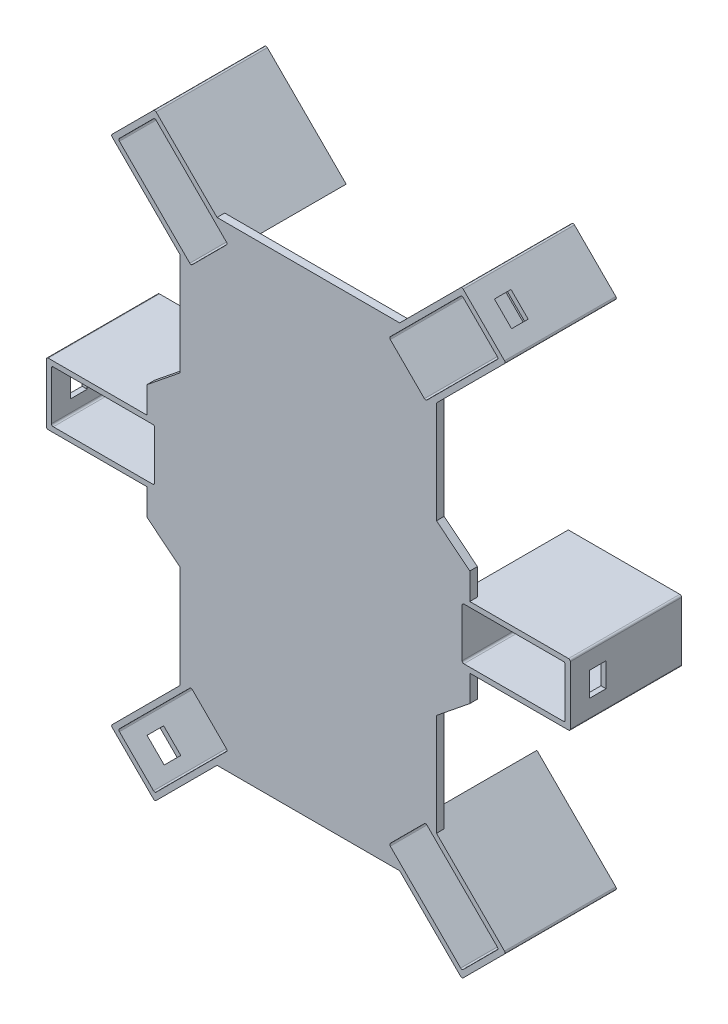
SolidWorks part; units mm, degrees
ref_plane "前视基准面" through (0, 0, 0) normal (0, 0, 1) x (1, 0, 0)
ref_plane "上视基准面" through (0, 0, 0) normal (0, 1, 0) x (1, 0, 0)
ref_plane "右视基准面" through (0, 0, 0) normal (1, 0, 0) x (0, 0, -1)
sketch "草图1" plane through (0, 0, 0) normal (0, 0, 1) x (1, 0, 0)
  line L0 (42.5, 0) -> (90.5, 0) construction
  line L1 (-42.5, 82.5) -> (42.5, 82.5)
  line L2 (-42.5, 82.5) -> (-42.5, -82.5)
  line L3 (-42.5, -82.5) -> (42.5, -82.5)
  line L4 (42.5, 82.5) -> (42.5, -82.5)
  line L5 (-42.5, 82.5) -> (42.5, -82.5) construction
  line L6 (-42.5, -82.5) -> (42.5, 82.5) construction
  line L7 (42.5, 82.5) -> (60.1777, 100.1777) construction
  line L8 (42.5, -82.5) -> (60.1777, -100.1777) construction
  line L9 (-42.5, 0) -> (-90.5, 0) construction
  line L10 (-42.5, -82.5) -> (-60.1777, -100.1777) construction
  line L11 (-42.5, 82.5) -> (-60.1777, 100.1777) construction
  line L12 (58.25, 12.15) -> (102.65, 12.15)
  line L13 (60.25, 10.15) -> (100.65, 10.15)
  line L14 (60.25, 10.15) -> (60.25, -10.15)
  line L15 (60.25, -10.15) -> (100.65, -10.15)
  line L16 (100.65, 10.15) -> (100.65, -10.15)
  line L17 (60.25, 10.15) -> (100.65, -10.15) construction
  line L18 (60.25, -10.15) -> (100.65, 10.15) construction
  line L19 (102.65, 12.15) -> (102.65, -12.15)
  line L20 (58.25, -12.15) -> (102.65, -12.15)
  line L21 (58.25, 12.15) -> (58.25, -12.15)
  line L22 (0, 0) -> (0, 51.9271) construction
  line L23 (-60.25, -10.15) -> (-100.65, 10.15) construction
  line L24 (-60.25, 10.15) -> (-100.65, -10.15) construction
  line L25 (-42.5, 0) -> (-90.5, 0) construction
  line L26 (-58.25, 12.15) -> (-58.25, -12.15)
  line L27 (-58.25, -12.15) -> (-102.65, -12.15)
  line L28 (-102.65, 12.15) -> (-102.65, -12.15)
  line L29 (-100.65, 10.15) -> (-100.65, -10.15)
  line L30 (-60.25, -10.15) -> (-100.65, -10.15)
  line L31 (-60.25, 10.15) -> (-60.25, -10.15)
  line L32 (-60.25, 10.15) -> (-100.65, 10.15)
  line L33 (-58.25, 12.15) -> (-102.65, 12.15)
  point P0 (0, 0)
  point P12 (80.45, 0)
  point P29 (-80.45, 0)
  dimension "D1" = 85
  dimension "D2" = 165
  dimension "D3" = 48
  dimension "D4" = 25
  dimension "D5" = 25
  dimension "D6" = 135
  dimension "D8" = 25
  dimension "D9" = 25
  dimension "D10" = 40.4
  dimension "D11" = 20.3
  dimension "D12" = 10.15
  dimension "D13" = 2
sketch "草图5" plane through (0, 0, 0) normal (0, 0, 1) x (1, 0, 0)
  line L0 (60.1777, 114.5319) -> (74.5319, 100.1777)
  line L1 (74.5319, 100.1777) -> (45.9648, 71.6106)
  line L2 (45.9648, 71.6106) -> (31.6106, 85.9648)
  line L3 (31.6106, 85.9648) -> (60.1777, 114.5319)
  line L4 (60.1777, 100.1777) -> (42.5, 82.5) construction
  line L5 (28.7821, 85.9648) -> (60.1777, 117.3604)
  line L6 (60.1777, 117.3604) -> (77.3604, 100.1777)
  line L7 (77.3604, 100.1777) -> (45.9648, 68.7821)
  line L8 (45.9648, 68.7821) -> (28.7821, 85.9648)
  line L9 (0, 0) -> (28.7821, 0) construction
  line L10 (60.1777, -100.1777) -> (42.5, -82.5) construction
  line L11 (45.9648, -68.7821) -> (28.7821, -85.9648)
  line L12 (77.3604, -100.1777) -> (45.9648, -68.7821)
  line L13 (60.1777, -117.3604) -> (77.3604, -100.1777)
  line L14 (28.7821, -85.9648) -> (60.1777, -117.3604)
  line L15 (31.6106, -85.9648) -> (60.1777, -114.5319)
  line L16 (45.9648, -71.6106) -> (31.6106, -85.9648)
  line L17 (74.5319, -100.1777) -> (45.9648, -71.6106)
  line L18 (60.1777, -114.5319) -> (74.5319, -100.1777)
  line L19 (0, 0) -> (0, 63.0262) construction
  line L20 (-60.1777, -100.1777) -> (-42.5, -82.5) construction
  line L21 (-60.1777, 100.1777) -> (-42.5, 82.5) construction
  line L22 (-60.1777, -114.5319) -> (-74.5319, -100.1777)
  line L23 (-74.5319, -100.1777) -> (-45.9648, -71.6106)
  line L24 (-45.9648, -71.6106) -> (-31.6106, -85.9648)
  line L25 (-31.6106, -85.9648) -> (-60.1777, -114.5319)
  line L26 (-28.7821, -85.9648) -> (-60.1777, -117.3604)
  line L27 (-60.1777, -117.3604) -> (-77.3604, -100.1777)
  line L28 (-77.3604, -100.1777) -> (-45.9648, -68.7821)
  line L29 (-45.9648, -68.7821) -> (-28.7821, -85.9648)
  line L30 (-45.9648, 68.7821) -> (-28.7821, 85.9648)
  line L31 (-77.3604, 100.1777) -> (-45.9648, 68.7821)
  line L32 (-60.1777, 117.3604) -> (-77.3604, 100.1777)
  line L33 (-28.7821, 85.9648) -> (-60.1777, 117.3604)
  line L34 (-31.6106, 85.9648) -> (-60.1777, 114.5319)
  line L35 (-45.9648, 71.6106) -> (-31.6106, 85.9648)
  line L36 (-74.5319, 100.1777) -> (-45.9648, 71.6106)
  line L37 (-60.1777, 114.5319) -> (-74.5319, 100.1777)
  dimension "D1" = 40.4
  dimension "D2" = 20.3
  dimension "D3" = 10.15
  dimension "D4" = 2
extrude "凸台-拉伸5" add sketch "草图1" along normal blind 42 contours L26 L33 L28 L27 L32 L31 L30 L29 | L12 L21 L20 L19 L13 L16 L15 L14 | L2 L3 L4 L1
extrude "凸台-拉伸6" add sketch "草图5" along normal blind 42
sketch "草图6" plane through (0, 0, 0) normal (0, 0, -1) x (-1, 0, 0)
  line L0 (-77.3604, 100.1777) -> (-60.1777, 117.3604)
  line L1 (-60.1777, 117.3604) -> (-28.7821, 85.9648)
  line L2 (-28.7821, 85.9648) -> (-45.9648, 68.7821)
  line L3 (-45.9648, 68.7821) -> (-77.3604, 100.1777)
  line L4 (-60.1777, 100.1777) -> (-55.3693, 95.3693) construction
  line L5 (-42.5, 82.5) -> (-60.1777, 100.1777) construction
  line L6 (-55.3693, 95.3693) -> (-61.0262, 89.7125) construction
  line L7 (-46.0214, 86.0214) -> (-50.9711, 81.0716) construction
  line L8 (-60.1777, 100.1777) -> (-41.0716, 81.0716) construction
  line L9 (-58.25, 12.15) -> (-58.25, -12.15)
  line L10 (-58.25, -12.15) -> (-102.65, -12.15)
  line L11 (-70.48, 0) -> (-70.48, -7) construction
  line L12 (-102.65, 12.15) -> (-58.25, 12.15)
  line L13 (-90.5, 0) -> (-83.7, 0) construction
  line L14 (-83.7, 0) -> (-83.7, -8) construction
  line L15 (-102.65, -12.15) -> (-102.65, 12.15)
  line L16 (-90.5, 0) -> (-63.48, 0) construction
  line L17 (0, 0) -> (28.8174, 0) construction
  line L18 (-60.1777, -100.1777) -> (-41.0716, -81.0716) construction
  line L19 (-46.0214, -86.0214) -> (-50.9711, -81.0716) construction
  line L20 (-55.3693, -95.3693) -> (-61.0262, -89.7125) construction
  line L21 (-60.1777, -100.1777) -> (-55.3693, -95.3693) construction
  line L22 (-45.9648, -68.7821) -> (-77.3604, -100.1777)
  line L23 (-28.7821, -85.9648) -> (-45.9648, -68.7821)
  line L24 (-60.1777, -117.3604) -> (-28.7821, -85.9648)
  line L25 (-77.3604, -100.1777) -> (-60.1777, -117.3604)
  line L26 (0, 0) -> (0, 41.0971) construction
  line L27 (0, 0) -> (0, 51.9271) construction
  line L28 (60.1777, -100.1777) -> (55.3693, -95.3693) construction
  line L29 (55.3693, -95.3693) -> (61.0262, -89.7125) construction
  line L30 (46.0214, -86.0214) -> (50.9711, -81.0716) construction
  line L31 (60.1777, -100.1777) -> (41.0716, -81.0716) construction
  line L32 (90.5, 0) -> (63.48, 0) construction
  line L33 (83.7, 0) -> (83.7, -8) construction
  line L34 (90.5, 0) -> (83.7, 0) construction
  line L35 (70.48, 0) -> (70.48, -7) construction
  line L36 (60.1777, 100.1777) -> (41.0716, 81.0716) construction
  line L37 (46.0214, 86.0214) -> (50.9711, 81.0716) construction
  line L38 (55.3693, 95.3693) -> (61.0262, 89.7125) construction
  line L39 (60.1777, 100.1777) -> (55.3693, 95.3693) construction
  line L40 (77.3604, -100.1777) -> (60.1777, -117.3604)
  line L41 (60.1777, -117.3604) -> (28.7821, -85.9648)
  line L42 (28.7821, -85.9648) -> (45.9648, -68.7821)
  line L43 (45.9648, -68.7821) -> (77.3604, -100.1777)
  line L44 (102.65, -12.15) -> (102.65, 12.15)
  line L45 (102.65, 12.15) -> (58.25, 12.15)
  line L46 (58.25, -12.15) -> (102.65, -12.15)
  line L47 (58.25, 12.15) -> (58.25, -12.15)
  line L48 (45.9648, 68.7821) -> (77.3604, 100.1777)
  line L49 (28.7821, 85.9648) -> (45.9648, 68.7821)
  line L50 (60.1777, 117.3604) -> (28.7821, 85.9648)
  line L51 (77.3604, 100.1777) -> (60.1777, 117.3604)
  circle A0 centre (-60.1777, 100.1777) radius 6.75
  circle A1 centre (-61.0262, 89.7125) radius 0.8
  circle A2 centre (-50.9711, 81.0716) radius 0.8
  circle A3 centre (-41.0716, 81.0716) radius 0.8
  circle A4 centre (-41.0716, 90.9711) radius 0.8
  circle A5 centre (-49.7125, 101.0262) radius 0.8
  circle A6 centre (-70.48, -7) radius 0.8
  circle A7 centre (-63.48, 0) radius 0.8
  circle A8 centre (-90.5, 0) radius 6.75
  circle A9 centre (-83.7, -8) radius 0.8
  circle A10 centre (-70.48, 7) radius 0.8
  circle A11 centre (-83.7, 8) radius 0.8
  circle A12 centre (-49.7125, -101.0262) radius 0.8
  circle A13 centre (-41.0716, -90.9711) radius 0.8
  circle A14 centre (-41.0716, -81.0716) radius 0.8
  circle A15 centre (-50.9711, -81.0716) radius 0.8
  circle A16 centre (-61.0262, -89.7125) radius 0.8
  circle A17 centre (-60.1777, -100.1777) radius 6.75
  circle A18 centre (60.1777, -100.1777) radius 6.75
  circle A19 centre (61.0262, -89.7125) radius 0.8
  circle A20 centre (50.9711, -81.0716) radius 0.8
  circle A21 centre (41.0716, -81.0716) radius 0.8
  circle A22 centre (41.0716, -90.9711) radius 0.8
  circle A23 centre (49.7125, -101.0262) radius 0.8
  circle A24 centre (83.7, 8) radius 0.8
  circle A25 centre (70.48, 7) radius 0.8
  circle A26 centre (83.7, -8) radius 0.8
  circle A27 centre (90.5, 0) radius 6.75
  circle A28 centre (63.48, 0) radius 0.8
  circle A29 centre (70.48, -7) radius 0.8
  circle A30 centre (49.7125, 101.0262) radius 0.8
  circle A31 centre (41.0716, 90.9711) radius 0.8
  circle A32 centre (41.0716, 81.0716) radius 0.8
  circle A33 centre (50.9711, 81.0716) radius 0.8
  circle A34 centre (61.0262, 89.7125) radius 0.8
  circle A35 centre (60.1777, 100.1777) radius 6.75
  dimension "D1" = 13.5
  dimension "D4" = 1.6
  dimension "D7" = 1.6
  dimension "D9" = 1.6
  dimension "D2" = 6.8
  dimension "D3" = 8
  dimension "D5" = 7
  dimension "D6" = 20.02
  dimension "D8" = 27.02
extrude "凸台-拉伸8" add sketch "草图6" along normal blind 1.6
fillet "圆角1" radius 0.7 4 edges at (31.6106, 85.9648, 21) (45.9648, 71.6106, 21) (60.1777, 114.5319, 21) (74.5319, 100.1777, 21)
fillet "圆角2" radius 0.7 4 edges at (-74.5319, 100.1777, 21) (-60.1777, 114.5319, 21) (-45.9648, 71.6106, 21) (-31.6106, 85.9648, 21)
fillet "圆角3" radius 0.7 4 edges at (-60.25, -10.15, 21) (-100.65, -10.15, 21) (-100.65, 10.15, 21) (-60.25, 10.15, 21)
fillet "圆角4" radius 0.7 4 edges at (-60.1777, -114.5319, 21) (-74.5319, -100.1777, 21) (-45.9648, -71.6106, 21) (-31.6106, -85.9648, 21)
fillet "圆角5" radius 0.7 4 edges at (60.1777, -114.5319, 21) (74.5319, -100.1777, 21) (45.9648, -71.6106, 21) (31.6106, -85.9648, 21)
fillet "圆角6" radius 0.7 4 edges at (60.25, 10.15, 21) (60.25, -10.15, 21) (100.65, -10.15, 21) (100.65, 10.15, 21)
sketch "草图7" plane through (0, 0, -1.6) normal (0, 0, -1) x (-1, 0, 0)
  line L0 (0, 0) -> (0, -53.3863) construction
  circle A4 centre (83.7, 8) radius 2
  circle A5 centre (83.7, -8) radius 2
  circle A6 centre (61.0262, -89.7125) radius 2
  circle A7 centre (49.7125, -101.0262) radius 2
  circle A8 centre (-49.7125, -101.0262) radius 2
  circle A9 centre (-61.0262, -89.7125) radius 2
  circle A10 centre (-83.7, -8) radius 2
  circle A11 centre (-83.7, 8) radius 2
  circle A14 centre (-61.0262, 89.7125) radius 2
  circle A15 centre (-49.7125, 101.0262) radius 2
  circle A16 centre (49.7125, 101.0262) radius 2
  circle A17 centre (61.0262, 89.7125) radius 2
  dimension "D3" = 4
  dimension "D4" = 4
  dimension "D5" = 4
  dimension "D6" = 4
  dimension "D7" = 4
  dimension "D8" = 4
  dimension "D9" = 4
  dimension "D10" = 4
extrude "切除-拉伸2" cut sketch "草图7" against normal blind 0.7
sketch "草图8" plane through (-88.769, -88.769, 0) normal (-0.7071, -0.7071, 0) x (0, 0, 1)
  line L0 (-1.6, -28.2843) -> (42, -28.2843) construction
  line L1 (-1.6, -40.4343) -> (-1.6, -16.1343) construction
  line L2 (42, -16.1343) -> (42, -40.4343) construction
  line L4 (28, -23.5343) -> (34.5, -23.5343)
  line L5 (28, -23.5343) -> (28, -33.0343)
  line L6 (28, -33.0343) -> (34.5, -33.0343)
  line L7 (34.5, -23.5343) -> (34.5, -33.0343)
  dimension "D1" = 7.5
  dimension "D2" = 9.5
  dimension "D3" = 6.5
extrude "切除-拉伸3" cut sketch "草图8" against normal blind 9.8
sketch "草图9" plane through (-102.65, 0, 0) normal (-1, 0, 0) x (0, 0, 1)
  line L0 (42, 12.15) -> (42, -12.15) construction
  line L1 (28, 4.75) -> (34.5, 4.75)
  line L2 (28, 4.75) -> (28, -4.75)
  line L3 (28, -4.75) -> (34.5, -4.75)
  line L4 (34.5, 4.75) -> (34.5, -4.75)
  line L5 (42, 0) -> (20.8942, 0) construction
  dimension "D1" = 6.5
  dimension "D2" = 7.5
  dimension "D3" = 9.5
extrude "切除-拉伸4" cut sketch "草图9" against normal blind 9.8
sketch "草图10" plane through (-88.769, 88.769, 0) normal (-0.7071, 0.7071, 0) x (0, 0, 1)
  line L0 (42, 28.2843) -> (10.5352, 28.2843) construction
  line L1 (42, 40.4343) -> (42, 16.1343) construction
  line L3 (28, 33.0559) -> (34.5, 33.0559)
  line L4 (28, 33.0559) -> (28, 23.5559)
  line L5 (28, 23.5559) -> (34.5, 23.5559)
  line L6 (34.5, 33.0559) -> (34.5, 23.5559)
  dimension "D1" = 7.5
  dimension "D2" = 6.5
  dimension "D3" = 9.5
extrude "切除-拉伸5" cut sketch "草图10" against normal blind 9.8
sketch "草图11" plane through (88.769, 88.769, 0) normal (0.7071, 0.7071, 0) x (0, 0, -1)
  line L0 (1.6, 40.4343) -> (1.6, 16.1343) construction
  line L1 (-34.5, 33.0343) -> (-28, 33.0343)
  line L2 (-34.5, 33.0343) -> (-34.5, 23.5343)
  line L3 (-34.5, 23.5343) -> (-28, 23.5343)
  line L4 (-28, 33.0343) -> (-28, 23.5343)
  line L5 (1.6, 28.2843) -> (-24.8278, 28.2843) construction
  line L6 (-42, 16.1343) -> (-42, 40.4343) construction
  dimension "D1" = 6.5
  dimension "D2" = 9.5
  dimension "D3" = 7.5
extrude "切除-拉伸6" cut sketch "草图11" against normal blind 9.8
sketch "草图12" plane through (102.65, 0, 0) normal (1, 0, 0) x (0, 0, -1)
  line L0 (-42, 12.15) -> (-42, -12.15) construction
  line L1 (-34.5, 4.75) -> (-28, 4.75)
  line L2 (-34.5, 4.75) -> (-34.5, -4.75)
  line L3 (-34.5, -4.75) -> (-28, -4.75)
  line L4 (-28, 4.75) -> (-28, -4.75)
  line L5 (-42, 0) -> (-21.0394, 0) construction
  dimension "D1" = 6.5
  dimension "D2" = 7.5
  dimension "D3" = 9.5
extrude "切除-拉伸7" cut sketch "草图12" against normal blind 9.8
sketch "草图13" plane through (88.769, -88.769, 0) normal (0.7071, -0.7071, 0) x (0, 0, -1)
  line L0 (-42, -28.2843) -> (-21.5674, -28.2843) construction
  line L1 (-42, -40.4343) -> (-42, -16.1343) construction
  line L3 (-34.5, -23.5343) -> (-28, -23.5343)
  line L4 (-34.5, -23.5343) -> (-34.5, -33.0343)
  line L5 (-34.5, -33.0343) -> (-28, -33.0343)
  line L6 (-28, -23.5343) -> (-28, -33.0343)
  dimension "D1" = 6.5
  dimension "D2" = 7.5
  dimension "D3" = 9.5
extrude "切除-拉伸8" cut sketch "草图13" against normal blind 9.8
fillet "圆角7" radius 0.7 2 edges at (-77.3604, 100.1777, 20.2) (-60.1777, 117.3604, 20.2)
fillet "圆角8" radius 0.7 2 edges at (-102.65, -12.15, 20.2) (-102.65, 12.15, 20.2)
fillet "圆角9" radius 0.7 2 edges at (-60.1777, -117.3604, 20.2) (-77.3604, -100.1777, 20.2)
fillet "圆角10" radius 0.7 2 edges at (77.3604, -100.1777, 20.2) (60.1777, -117.3604, 20.2)
fillet "圆角11" radius 0.7 2 edges at (102.65, 12.15, 20.2) (102.65, -12.15, 20.2)
fillet "圆角12" radius 0.7 2 edges at (60.1777, 117.3604, 20.2) (77.3604, 100.1777, 20.2)
sketch "草图14" plane through (0, 0, 42) normal (0, 0, 1) x (1, 0, 0)
  line L0 (58.25, 12.15) -> (42.5, 24.8626)
  line L1 (-25.3173, 82.5) -> (25.3173, 82.5)
  line L2 (-42.5, 65.3173) -> (-42.5, 24.8626)
  line L3 (-25.3173, -82.5) -> (25.3173, -82.5)
  line L4 (42.5, 65.3173) -> (42.5, 24.8626)
  line L5 (58.25, -12.15) -> (58.25, 12.15)
  line L6 (58.25, -12.15) -> (102.65, -12.15) construction
  line L7 (58.25, -12.15) -> (42.5, -24.8626)
  line L8 (0, 0) -> (25.9785, 0) construction
  line L9 (0, 0) -> (0, 16.1012) construction
  line L11 (0, 0) -> (0, 51.9271) construction
  line L12 (-28.7821, 85.9648) -> (-25.3173, 82.5)
  line L13 (-28.7821, 85.9648) -> (-45.9648, 68.7821)
  line L14 (-45.9648, 68.7821) -> (-42.5, 65.3173)
  line L15 (28.7821, 85.9648) -> (25.3173, 82.5)
  line L16 (28.7821, 85.9648) -> (45.9648, 68.7821)
  line L17 (45.9648, 68.7821) -> (42.5, 65.3173)
  line L18 (45.9648, -68.7821) -> (42.5, -65.3173)
  line L19 (28.7821, -85.9648) -> (25.3173, -82.5)
  line L20 (28.7821, -85.9648) -> (45.9648, -68.7821)
  line L21 (-45.9648, -68.7821) -> (-42.5, -65.3173)
  line L22 (-28.7821, -85.9648) -> (-45.9648, -68.7821)
  line L23 (-28.7821, -85.9648) -> (-25.3173, -82.5)
  line L24 (-58.25, -12.15) -> (-42.5, -24.8626)
  line L25 (-58.25, -12.15) -> (-58.25, 12.15)
  line L26 (-58.25, 12.15) -> (-42.5, 24.8626)
  line L27 (-42.5, -24.8626) -> (-42.5, -65.3173)
  line L28 (42.5, -24.8626) -> (42.5, -65.3173)
extrude "凸台-拉伸9" add sketch "草图14" against normal blind 3
sketch "草图19" plane through (0, 0, 39) normal (0, 0, -1) x (-1, 0, 0)
  line L0 (-50.2075, 73.0248) -> (-50.2075, 33.0248)
  line L1 (-76.8654, 99.6827) -> (-45.9648, 68.7821) construction
  line L2 (-50.2075, 33.0248) -> (-58.25, 26.5333)
  line L3 (-58.25, 26.5333) -> (-58.25, 12.15)
  line L4 (-58.25, 12.15) -> (-42.5, 24.8626) construction
  line L5 (-50.2075, 73.0248) -> (-45.9648, 68.7821)
  line L6 (-45.9648, 68.7821) -> (-28.7821, 85.9648)
  line L7 (-28.7821, 85.9648) -> (28.7821, 85.9648)
  line L8 (28.7821, 85.9648) -> (45.9648, 68.7821)
  line L9 (0, 85.9648) -> (0, -134.9503) construction
  line L10 (0, 0) -> (40.7748, 0) construction
  line L11 (28.7821, -85.9648) -> (45.9648, -68.7821)
  line L12 (-28.7821, -85.9648) -> (28.7821, -85.9648)
  line L13 (-45.9648, -68.7821) -> (-28.7821, -85.9648)
  line L14 (-50.2075, -73.0248) -> (-45.9648, -68.7821)
  line L15 (-58.25, -26.5333) -> (-58.25, -12.15)
  line L16 (-50.2075, -33.0248) -> (-58.25, -26.5333)
  line L17 (-50.2075, -73.0248) -> (-50.2075, -33.0248)
  line L18 (50.2075, -73.0248) -> (45.9648, -68.7821)
  line L19 (50.2075, -73.0248) -> (50.2075, -33.0248)
  line L20 (50.2075, -33.0248) -> (58.25, -26.5333)
  line L21 (58.25, -26.5333) -> (58.25, -12.15)
  line L22 (58.25, 26.5333) -> (58.25, 12.15)
  line L23 (50.2075, 33.0248) -> (58.25, 26.5333)
  line L24 (50.2075, 73.0248) -> (50.2075, 33.0248)
  line L25 (50.2075, 73.0248) -> (45.9648, 68.7821)
  line L26 (58.25, 12.15) -> (58.25, -12.15)
  line L27 (-58.25, 12.15) -> (-58.25, -12.15)
  dimension "D1" = 6
  dimension "D2" = 40
extrude "凸台-拉伸11" add sketch "草图19" against normal up to vertex (3 mm away)
sketch "草图20" plane through (0, 0, 39) normal (0, 0, -1) x (-1, 0, 0)
  line L0 (-28.7821, 85.9648) -> (-35.7821, 92.9648)
  line L1 (-28.7821, 85.9648) -> (-59.6827, 116.8654) construction
  line L2 (-35.7821, 92.9648) -> (35.7821, 92.9648)
  line L3 (59.6827, 116.8654) -> (28.7821, 85.9648) construction
  line L4 (35.7821, 92.9648) -> (28.7821, 85.9648)
  line L5 (28.7821, 85.9648) -> (-28.7821, 85.9648)
  line L6 (-58.25, 0) -> (41.7659, 0) construction
  line L7 (-58.25, -12.15) -> (-58.25, 12.15) construction
  line L8 (-28.7821, -85.9648) -> (-35.7821, -92.9648)
  line L9 (35.7821, -92.9648) -> (28.7821, -85.9648)
  line L10 (-35.7821, -92.9648) -> (35.7821, -92.9648)
  line L11 (28.7821, -85.9648) -> (-28.7821, -85.9648)
  dimension "D1" = 7
extrude "凸台-拉伸12" add sketch "草图20" against normal up to vertex (3 mm away)
sketch "草图21" plane through (0, 0, 42) normal (0, 0, 1) x (1, 0, 0)
  line L0 (-58.25, 26.5333) -> (-63.25, 22.4975)
  line L1 (-63.25, 22.4975) -> (-63.25, 12.15)
  line L2 (-58.25, 12.15) -> (-101.95, 12.15) construction
  line L3 (-63.25, 12.15) -> (-58.25, 12.15)
  line L4 (-58.25, 12.15) -> (-58.25, 26.5333)
  line L5 (-58.25, 26.5333) -> (-50.2075, 33.0248) construction
  line L6 (-60.25, 0) -> (-30.6569, 0) construction
  line L7 (-60.25, 9.45) -> (-60.25, -9.45) construction
  line L8 (-63.25, -22.4975) -> (-63.25, -12.15)
  line L9 (-63.25, -12.15) -> (-58.25, -12.15)
  line L10 (-58.25, -12.15) -> (-58.25, -26.5333)
  line L11 (-58.25, -26.5333) -> (-63.25, -22.4975)
  line L12 (0, 0) -> (0, -27.8132) construction
  line L13 (60.25, 0) -> (30.6569, 0) construction
  line L14 (58.25, -26.5333) -> (63.25, -22.4975)
  line L15 (58.25, -12.15) -> (58.25, -26.5333)
  line L16 (63.25, -12.15) -> (58.25, -12.15)
  line L17 (63.25, -22.4975) -> (63.25, -12.15)
  line L18 (58.25, 12.15) -> (58.25, 26.5333)
  line L19 (63.25, 12.15) -> (58.25, 12.15)
  line L20 (63.25, 22.4975) -> (63.25, 12.15)
  line L21 (58.25, 26.5333) -> (63.25, 22.4975)
  dimension "D1" = 5
extrude "凸台-拉伸13" add sketch "草图21" against normal up to vertex
sketch "草图22" plane through (0, 0, 42) normal (0, 0, 1) x (1, 0, 0)
  line L1 (-37.5, -80) -> (37.5, -80)
  line L2 (-37.5, -80) -> (-37.5, 80)
  line L3 (-37.5, 80) -> (37.5, 80)
  line L4 (37.5, -80) -> (37.5, 80)
  line L5 (-37.5, -80) -> (37.5, 80) construction
  line L6 (-37.5, 80) -> (37.5, -80) construction
  point P0 (0, 0)
  dimension "D1" = 160
  dimension "D2" = 75
sketch "草图23" plane through (0, 0, 39) normal (0, 0, -1) x (-1, 0, 0)
  line L1 (-50.2075, 53.0248) -> (-50.2075, 92.9648) construction
  line L2 (-50.2075, 73.0248) -> (-50.2075, 33.0248) construction
  line L3 (-50.2075, 92.9648) -> (50.2075, 92.9648) construction
  line L4 (50.2075, 92.9648) -> (50.2075, -92.9648) construction
  line L5 (50.2075, -92.9648) -> (-50.2075, -92.9648) construction
  line L6 (-50.2075, -92.9648) -> (-50.2075, 92.9648) construction
  dimension "D1" = 185.9296
  dimension "D2" = 100.4149
